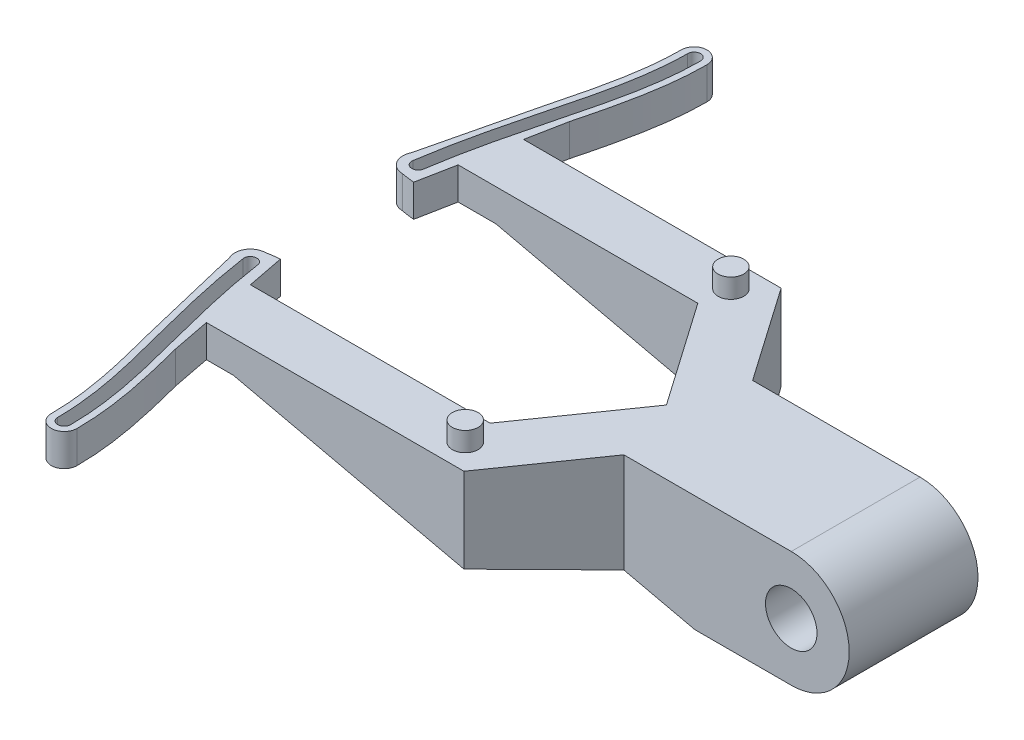
SolidWorks part; units mm, degrees
ref_plane "Front Plane" through (0, 0, 0) normal (0, 0, 1) x (1, 0, 0)
ref_plane "Top Plane" through (0, 0, 0) normal (0, 1, 0) x (1, 0, 0)
ref_plane "Right Plane" through (0, 0, 0) normal (1, 0, 0) x (0, 0, -1)
sketch "Sketch1" plane through (0, 0, 0) normal (0, 0, 1) x (1, 0, 0)
  line L0 (0, 9) -> (-90, 9)
  line L1 (-90, 9) -> (-90, -9)
  line L2 (-90, -9) -> (0, -9)
  circle A0 centre (0, 0) radius 4
  arc A1 (0, -9) -> (0, 9) centre (0, 0) ccw
  dimension "D1" = 8
  dimension "D2" = 5
  dimension "D3" = 90
extrude "Boss-Extrude1" add sketch "Sketch1" along normal blind 20
sketch "Sketch2" plane through (0, 9, 0) normal (0, 1, 0) x (1, 0, 0)
  line L0 (0, -20) -> (0, 0) construction
  line L1 (-90, -20) -> (-90, 0) construction
  circle A0 centre (-40, -10) radius 2
  point P4 (0, -10)
  dimension "D2" = 4
  dimension "D1" = 50
extrude "Boss-Extrude2" add sketch "Sketch2" along normal blind 3
ref_plane "Plane1" through (0, 0, 10) normal (0, 0, 1) x (1, 0, 0)
sketch "Sketch3" plane through (0, 9, 0) normal (0, 1, 0) x (1, 0, 0)
  arc A0 (-79.9711, -2.2655) -> (-81.9488, -2.5635) centre (-80.96, -2.4145) ccw construction
  arc A1 (-75, -38.2843) -> (-73, -38.2843) centre (-74, -38.2843) ccw construction
  arc A2 (-79.9711, -2.2655) -> (-81.9488, -2.5635) centre (-80.96, -2.4145) ccw
  arc A3 (-75, -38.2843) -> (-73, -38.2843) centre (-74, -38.2843) ccw
  spline S0 degree 3 poles (-1058.986, -216.5271) (-109.0048, -131.024) (-64.0898, -75.4075) (-77.9782, -20.5413) (-99.7429, 62.803) (-55.3261, 166.5834) (918.0383, -6.3644) knots -2.678519 -2.678519 -2.678519 -2.678519 0.171177 0.342354 0.513531 4.98778 4.98778 4.98778 4.98778 only from (-75, -38.2843) to (-81.9488, -2.5635) construction
  spline S1 degree 3 poles (-997.1438, 343.7577) (-127.7582, -141.7513) (-66.1774, -78.2682) (-74.1602, -27.4614) (-76.0502, -20.0135) (-97.6974, 62.9713) (-50.8864, 152.8882) (816.1568, 441.5093) knots -2.49455 -2.49455 -2.49455 -2.49455 0.085589 0.171177 0.342354 0.513531 5.001725 5.001725 5.001725 5.001725 only from (-73, -38.2843) to (-79.9711, -2.2655) construction
  spline S2 degree 3 poles (-75, -38.2843) (-75, -35.3) (-75.7439, -29.368) (-77.9782, -20.5413) (-80.2987, -11.6553) (-81.4904, -5.6043) (-81.9488, -2.5635) knots 0 0 0 0 0.171177 0.342354 0.513531 0.684708 0.684708 0.684708 0.684708
  spline S3 degree 3 poles (-73, -38.2843) (-73, -36.7233) (-73.1968, -33.5927) (-74.1602, -27.4614) (-76.0502, -20.0135) (-78.3515, -11.1915) (-79.5202, -5.2568) (-79.9711, -2.2655) knots 0 0 0 0 0.085589 0.171177 0.342354 0.513531 0.684708 0.684708 0.684708 0.684708
extrude "Cut-Extrude1" cut sketch "Sketch3" against normal blind 3
sketch "Sketch4" plane through (0, 9, 0) normal (0, 1, 0) x (1, 0, 0)
  line L0 (-90, -10) -> (-90, -0.4145) construction
  line L1 (-90, -0.4145) -> (-80.96, -0.4145) construction
  line L2 (-90, -10) -> (-90, -0.4145)
  line L3 (-90, -0.4145) -> (-80.96, -0.4145)
  line L4 (-81.5945, -10) -> (-90, -10)
  arc A0 (-78.9823, -2.1164) -> (-80.96, -0.4145) centre (-80.96, -2.4145) ccw construction
  arc A1 (-76, -38.2843) -> (-72, -38.2843) centre (-74, -38.2843) ccw construction
  arc A2 (-75, -38.2843) -> (-73, -38.2843) centre (-74, -38.2843) ccw
  arc A3 (-79.9711, -2.2655) -> (-81.9488, -2.5635) centre (-80.96, -2.4145) ccw
  arc A4 (-75, -38.2843) -> (-73, -38.2843) centre (-74, -38.2843) ccw
  arc A5 (-79.9711, -2.2655) -> (-81.9488, -2.5635) centre (-80.96, -2.4145) ccw
  arc A6 (-78.9823, -2.1164) -> (-80.96, -0.4145) centre (-80.96, -2.4145) ccw
  arc A7 (-76, -38.2843) -> (-72, -38.2843) centre (-74, -38.2843) ccw
  spline S0 degree 3 poles (-924.2832, -567.8224) (-132.4951, -117.4189) (-69.3296, -77.7794) (-77.0937, -28.1071) (-78.9424, -20.8077) (-100.3157, 61.0336) (-59.3823, 168.2132) (903.102, -184.2253) knots -2.571912 -2.571912 -2.571912 -2.571912 0.085589 0.171177 0.342354 0.513531 4.882226 4.882226 4.882226 4.882226 only from (-76, -38.2843) to (-81.5945, -10) construction
  spline S1 degree 3 poles (-904.2098, 516.1708) (-121.0944, -143.2537) (-65.4526, -76.3627) (-73.1823, -27.2462) (-75.0861, -19.7488) (-96.1499, 61.0308) (-51.0219, 141.9525) (701.6841, 622.817) knots -2.356734 -2.356734 -2.356734 -2.356734 0.085589 0.171177 0.342354 0.513531 4.89104 4.89104 4.89104 4.89104 only from (-72, -38.2843) to (-78.9823, -2.1164) construction
  spline S2 degree 3 poles (1897.9966, -205.483) (-28.5485, 220.8025) (-105.0736, 83.2161) (-77.9782, -20.5413) (-60.709, -88.7634) (-135.9521, -159.8796) (-2055.8753, -294.4418) knots -5.482781 -5.482781 -5.482781 -5.482781 0.171177 0.342354 0.513531 4.140256 4.140256 4.140256 4.140256 only from (-81.9488, -2.5635) to (-75, -38.2843)
  spline S3 degree 3 poles (-1860.5903, 848.0748) (-163.4311, -174.9591) (-64.2753, -90.3742) (-74.1602, -27.4614) (-76.0502, -20.0135) (-103.4056, 84.854) (-20.2326, 202.7897) (1770.3584, 740.4726) knots -3.170514 -3.170514 -3.170514 -3.170514 0.085589 0.171177 0.342354 0.513531 6.275519 6.275519 6.275519 6.275519 only from (-73, -38.2843) to (-79.9711, -2.2655)
  spline S4 degree 3 poles (-81.9488, -2.5635) (-81.4904, -5.6043) (-80.2987, -11.6553) (-77.9782, -20.5413) (-75.7439, -29.368) (-75, -35.3) (-75, -38.2843) knots 0 0 0 0 0.171177 0.342354 0.513531 0.684708 0.684708 0.684708 0.684708
  spline S5 degree 3 poles (-73, -38.2843) (-73, -36.7233) (-73.1968, -33.5927) (-74.1602, -27.4614) (-76.0502, -20.0135) (-78.3515, -11.1915) (-79.5202, -5.2568) (-79.9711, -2.2655) knots 0 0 0 0 0.085589 0.171177 0.342354 0.513531 0.684708 0.684708 0.684708 0.684708
  spline S6 degree 3 poles (-76, -38.2843) (-76, -36.8322) (-76.1816, -33.9423) (-77.0937, -28.1071) (-78.9424, -20.8077) (-80.6538, -14.2546) (-81.4618, -10.6169) (-81.5945, -10) knots 0 0 0 0 0.085589 0.171177 0.342354 0.513531 0.548394 0.548394 0.548394 0.548394
  spline S7 degree 3 poles (-72, -38.2843) (-72, -36.6869) (-72.2019, -33.4762) (-73.1823, -27.2462) (-75.0861, -19.7488) (-77.3779, -10.9598) (-78.5351, -5.083) (-78.9823, -2.1164) knots 0 0 0 0 0.085589 0.171177 0.342354 0.513531 0.684708 0.684708 0.684708 0.684708
  dimension "D1" = 0
extrude "Boss-Extrude3" add sketch "Sketch4" against normal blind 5
sketch "Sketch5" plane through (0, 9, 0) normal (0, 1, 0) x (1, 0, 0)
  line L0 (-79.162, -20) -> (-83.1319, -3.47)
  line L2 (-81, 0) -> (-90, 0)
  line L3 (-90, 0) -> (-90, -20)
  line L4 (-90, -20) -> (-79.162, -20)
  line L9 (0, 0) -> (-90, 0) construction
  arc A1 (-83.1319, -3.47) -> (-81, 0) centre (-80.96, -2.4145) cw
  point P3 (-81.6537, 2.0855)
  point P4 (-81.3073, 0)
  point P9 (0, 0)
  point P10 (-90, 0)
  point P11 (-80.2234, 0)
  point P14 (0, 0)
  point P21 (0, 0)
  dimension "D1" = 9
  dimension "D2" = 17
extrude "Cut-Extrude2" cut sketch "Sketch5" against normal through all both and the other way through all
sketch "Sketch6" plane through (0, 4, 0) normal (0, -1, 0) x (1, 0, 0)
  line L0 (-76.0642, 20) -> (-78.1293, 20)
  line L2 (-76.0642, 20) -> (-75.0316, 20)
  line L3 (-79.162, 20) -> (-78.1293, 20)
  line L4 (-76.0642, 20) -> (-75.0316, 20)
  line L5 (-79.162, 20) -> (-78.1293, 20)
  arc A2 (-72, 38.2843) -> (-76, 38.2843) centre (-74, 38.2843) ccw
  arc A3 (-73, 38.2843) -> (-75, 38.2843) centre (-74, 38.2843) ccw
  arc A4 (-72, 38.2843) -> (-76, 38.2843) centre (-74, 38.2843) ccw
  spline S4 degree 3 poles (2795.9461, -835.4887) (-229.3066, -79.626) (-85.6163, -51.7622) (-62.4102, 95.6948) (-178.9666, 203.1646) (-2395.3069, -1848.8465) knots -4.345895 -4.345895 -4.345895 -4.345895 0.167009 0.252598 3.757273 3.757273 3.757273 3.757273 only from (-75.0316, 20) to (-72, 38.2843)
  spline S5 degree 3 poles (-2661.742, 1558.252) (-207.189, 153.0143) (-65.9043, 99.6935) (-77.0937, 28.1071) (-100.7939, -65.4676) (-142.5904, -184.4531) (2822.4838, -702.7417) knots -3.666677 -3.666677 -3.666677 -3.666677 0.276523 0.362112 0.533289 5.762588 5.762588 5.762588 5.762588 only from (-76, 38.2843) to (-79.162, 20)
  spline S6 degree 3 poles (834.6138, -388.5308) (-116.5891, -108.937) (-93.0075, -38.8322) (-64.0899, 75.4074) (-109.0046, 131.0238) (-1058.9793, 216.5265) knots -3.283095 -3.283095 -3.283095 -3.283095 0.342354 0.513531 3.363221 3.363221 3.363221 3.363221 only from (-78.1293, 20) to (-75, 38.2843)
  spline S7 degree 3 poles (-997.1437, -343.7577) (-127.7582, 141.7513) (-66.1774, 78.2682) (-74.1602, 27.4614) (-91.3888, -40.4307) (-110.9945, -97.2741) (802.7948, -457.0702) knots -2.49455 -2.49455 -2.49455 -2.49455 0.085589 0.171177 0.342354 3.98654 3.98654 3.98654 3.98654 only from (-73, 38.2843) to (-76.0642, 20)
  spline S8 degree 3 poles (-75.0316, 20) (-74.2876, 22.8938) (-73.1704, 27.322) (-72.2019, 33.4762) (-72, 36.6869) (-72, 38.2843) knots 0 0 0 0 0.167009 0.252598 0.338186 0.338186 0.338186 0.338186
  spline S9 degree 3 poles (-76, 38.2843) (-76, 36.8322) (-76.1816, 33.9423) (-77.0937, 28.1071) (-78.2682, 23.4698) (-79.0949, 20.2605) (-79.162, 20) knots 0.190935 0.190935 0.190935 0.190935 0.276523 0.362112 0.533289 0.548394 0.548394 0.548394 0.548394
  dimension "D1" = 0
extrude "Boss-Extrude4" add sketch "Sketch6" against normal blind 2
sketch "Sketch7" plane through (0, 0, 20) normal (0, 0, 1) x (1, 0, 0)
  line L0 (-72, -21) -> (-15, -9)
  line L1 (-92, -21) -> (-72, -21)
  line L2 (-92, -21) -> (-92, 4)
  line L3 (-92, 4) -> (-72, 4)
  line L4 (-72, -21) -> (-72, 4) construction
  line L5 (-79.162, -9) -> (0, -9) construction
  line L6 (-15, -9) -> (-72, 4)
  line L7 (-76, 4) -> (-72, 4) construction
  line L8 (-72, 4) -> (-72, 9) construction
  point P9 (0, 0)
  point P12 (-89.5, -20.5307)
  point P13 (-12.9376, -9)
  dimension "D1" = 20
  dimension "D2" = 25
  dimension "D3" = 15
extrude "Cut-Extrude3" cut sketch "Sketch7" against normal through all both and the other way through all
sketch "Sketch8" plane through (0, 0, 0) normal (0, 0, -1) x (-1, 0, 0)
  line L5 (15, -9) -> (72, 4)
  line L6 (72, 4) -> (81, 4)
  line L7 (81, 4) -> (81, 9)
  line L8 (81, 9) -> (0, 9)
  line L9 (0, -9) -> (15, -9)
  line L10 (15, -9) -> (72, 4)
  line L11 (72, 4) -> (81, 4)
  line L12 (81, 4) -> (81, 9)
  line L13 (81, 9) -> (0, 9)
  line L14 (0, -9) -> (15, -9)
  circle A0 centre (0, 0) radius 4
  arc A1 (0, 9) -> (0, -9) centre (0, 0) ccw
  arc A2 (0, 9) -> (0, -9) centre (0, 0) ccw
  circle A3 centre (0, 0) radius 4 construction
  dimension "D1" = 0
extrude "Boss-Extrude5" add sketch "Sketch8" along normal blind 30
sketch "Sketch9" plane through (0, 9, 0) normal (0, 1, 0) x (1, 0, 0)
  line L0 (9, -20) -> (9, 30) construction
  line L1 (9, 0.6262) -> (-26, 0.6262)
  line L2 (9, 0.6262) -> (9, 20.6262) construction
  line L3 (9, 20.6262) -> (-26, 20.6262) construction
  line L4 (-26, 0.6262) -> (-26, 20.6262) construction
  line L5 (-75.0316, -20) -> (-81, 10.6262) construction
  line L6 (-81, 30) -> (-81, 0) construction
  line L7 (0, -20) -> (-75.0316, -20) construction
  line L8 (-26, 0.6262) -> (-36.2009, -14)
  line L9 (-36.2009, -14) -> (-76.2009, -14)
  line L10 (-76.2009, -14) -> (-75.0316, -20)
  line L11 (-75.0316, -20) -> (16, -20)
  line L12 (16, -20) -> (16, 10.6262)
  line L14 (9, 10.6262) -> (9, 0.6262)
  line L15 (9, 10.6262) -> (-29.3887, 10.6262)
  line L16 (-29.3887, 10.6262) -> (-40.6358, -5.5)
  line L17 (-40.6358, -5.5) -> (-77.8573, -5.5)
  line L18 (-77.8573, -5.5) -> (-78.984, 0.2811)
  line L19 (-81, 0) -> (-81, 30)
  line L20 (-81, 30) -> (16, 30)
  line L21 (16, 30) -> (16, 10.6262)
  arc A0 (-81, 0) -> (-78.984, 0.2811) centre (-77.286, -19.2652) cw
  point P15 (-26, 10.6262)
  dimension "D1" = 30.6262
  dimension "D2" = 20
  dimension "D3" = 35
  dimension "D4" = 7
  dimension "D5" = 40
  dimension "D6" = 6
  dimension "D7" = 8.5
  dimension "D8" = 8.5
extrude "Cut-Extrude4" cut sketch "Sketch9" against normal through all both and the other way through all
mirror "Mirror1" about plane through (9, -9, -10.6262) normal (0, 0, 1) of bodies 109
